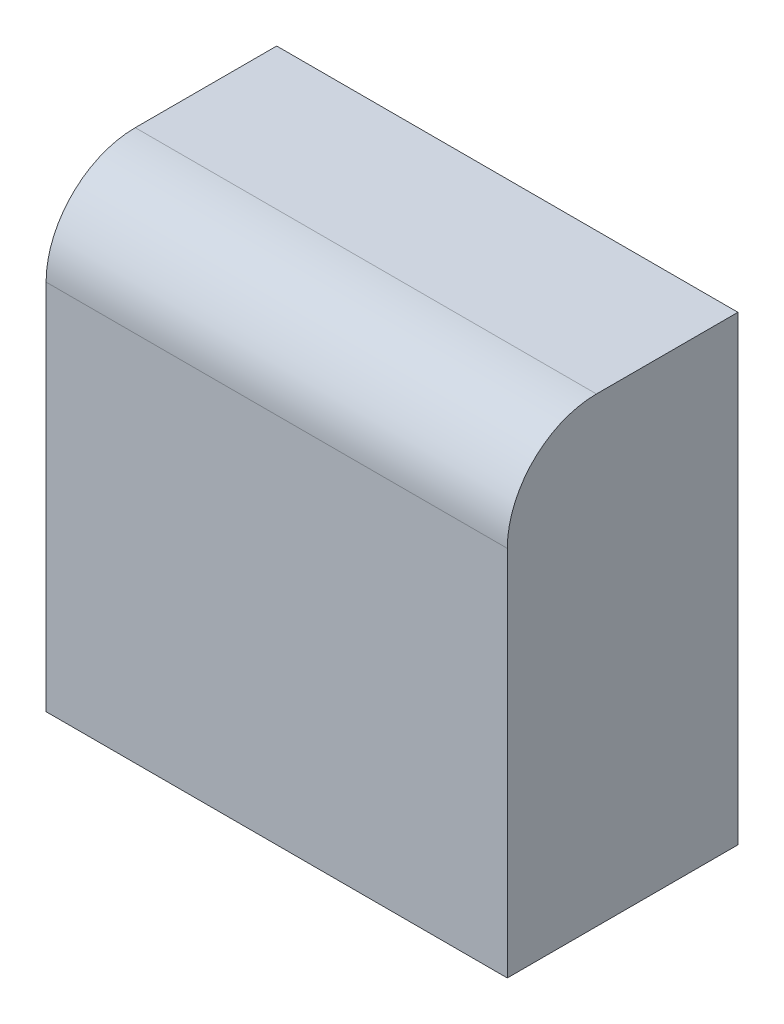
SolidWorks part; units mm, degrees
ref_plane "Plan de face" through (0, 0, 0) normal (0, 0, 1) x (1, 0, 0)
ref_plane "Plan de dessus" through (0, 0, 0) normal (0, 1, 0) x (1, 0, 0)
ref_plane "Plan de droite" through (0, 0, 0) normal (1, 0, 0) x (0, 0, -1)
sketch "Esquisse1" plane through (0, 0, 0) normal (0, 0, 1) x (1, 0, 0)
  line L1 (7.76, 7.76) -> (-7.76, 7.76)
  line L2 (7.76, 7.76) -> (7.76, -7.76)
  line L3 (7.76, -7.76) -> (-7.76, -7.76)
  line L4 (-7.76, 7.76) -> (-7.76, -7.76)
  line L5 (7.76, 7.76) -> (-7.76, -7.76) construction
  line L6 (7.76, -7.76) -> (-7.76, 7.76) construction
  point P0 (0, 0)
  dimension "D1" = 15.52
  dimension "D2" = 15.52
extrude "Boss.-Extru.1" add sketch "Esquisse1" along normal blind 7.76
fillet "Congé1" radius 3 1 edges at (0, 7.76, 7.76)
